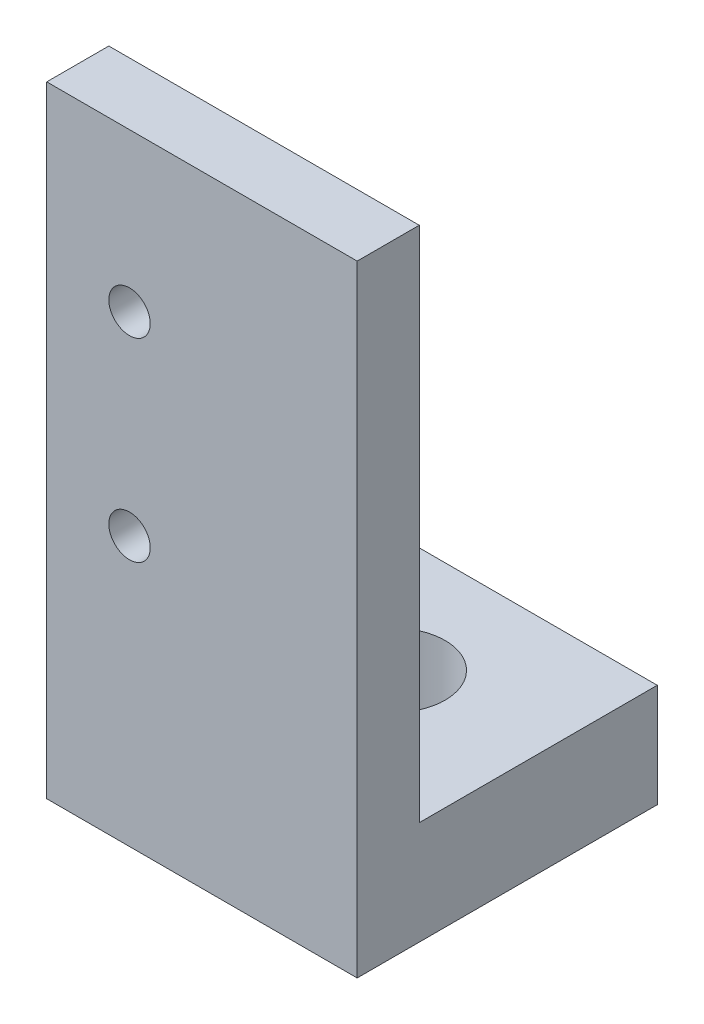
SolidWorks part; units mm, degrees
ref_plane "Front Plane" through (0, 0, 0) normal (0, 0, 1) x (1, 0, 0)
ref_plane "Top Plane" through (0, 0, 0) normal (0, 1, 0) x (1, 0, 0)
ref_plane "Right Plane" through (0, 0, 0) normal (1, 0, 0) x (0, 0, -1)
sketch "Croquis1" plane through (0, 0, 0) normal (0, 1, 0) x (1, 0, 0)
  line L0 (-8, 5.75) -> (-8, -5.75)
  line L1 (-8, 5.75) -> (8, 5.75)
  line L3 (-8, -5.75) -> (8, -5.75)
  line L4 (8, 5.75) -> (8, -5.75)
  line L5 (-8, 5.75) -> (8, -5.75) construction
  line L6 (-8, -5.75) -> (8, 5.75) construction
  line L7 (-8, -5.75) -> (-8, -8.75)
  line L8 (-8, -8.75) -> (8, -8.75)
  line L9 (8, -8.75) -> (8, -5.75)
  circle A0 centre (0, 0) radius 2.5
  point P0 (0, 0)
  dimension "D3" = 5
  dimension "D1" = 11.5
  dimension "D2" = 16
  dimension "D4" = 3
extrude "Saliente-Extruir1" add sketch "Croquis1" along normal blind 5
sketch "Croquis4" plane through (0, 5, 0) normal (0, 1, 0) x (1, 0, 0)
  line L0 (-8, -8.75) -> (-8, -5.75)
  line L1 (-8, 5.75) -> (-8, -8.75) construction
  line L2 (-8, -5.75) -> (8, -5.75)
  line L3 (8, 5.75) -> (8, -8.75) construction
  line L4 (8, -5.75) -> (8, -8.75)
  line L5 (8, -8.75) -> (-8, -8.75)
  dimension "D1" = 3
  dimension "D2" = 3
extrude "Saliente-Extruir3" add sketch "Croquis4" along normal blind 25
ref_plane "Plano1" through (-8, 0, 8.75) normal (0, -1, 0) x (-1, 0, 0)
sketch "Croquis6" plane through (0, 0, 8.75) normal (0, 0, 1) x (1, 0, 0)
  line L0 (-8, 30) -> (-8, 0) construction
  line L1 (-8, 0) -> (8, 0) construction
  circle A0 centre (-4, 22.38) radius 1
  circle A1 centre (-4, 13) radius 1
  dimension "D2" = 2
  dimension "D3" = 2
  dimension "D1" = 22.38
  dimension "D4" = 4
  dimension "D5" = 9.38
  dimension "D6" = 13
extrude "Cortar-Extruir1" cut sketch "Croquis6" against normal blind 25
sketch "Croquis7" plane through (0, 0, 8.75) normal (0, 0, 1) x (1, 0, 0)
  line L6 (8, 30) -> (7, 30)
  line L7 (-8, 30) -> (8, 30) construction
  line L8 (7, 30) -> (7, 0)
  line L9 (-8, 0) -> (8, 0) construction
  line L10 (7, 0) -> (8, 0)
  line L11 (8, 0) -> (8, 30)
  dimension "D1" = 1
extrude "Cortar-Extruir2" cut sketch "Croquis7" against normal blind 25
